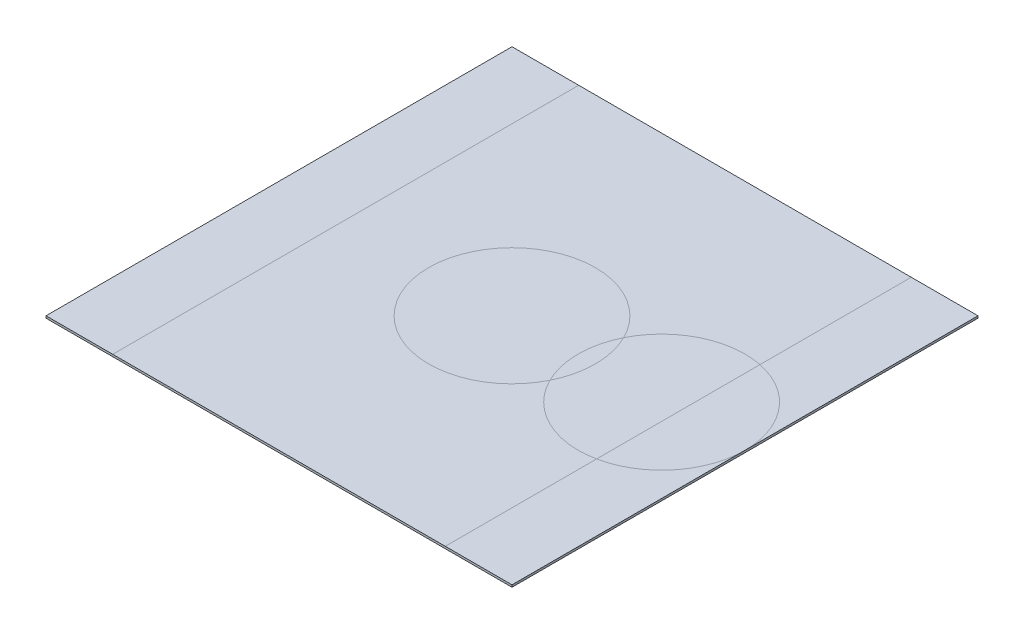
SolidWorks part; units mm, degrees
material "Zirconia"
ref_plane "Front Plane" through (0, 0, 0) normal (0, 0, 1) x (1, 0, 0)
ref_plane "Top Plane" through (0, 0, 0) normal (0, 1, 0) x (1, 0, 0)
ref_plane "Right Plane" through (0, 0, 0) normal (1, 0, 0) x (0, 0, -1)
sketch "Sketch1" plane through (0, 0, 0) normal (0, 1, 0) x (1, 0, 0)
  line L1 (-69.85, -69.85) -> (69.85, -69.85)
  line L2 (-69.85, -69.85) -> (-69.85, 69.85)
  line L3 (-69.85, 69.85) -> (69.85, 69.85)
  line L4 (69.85, -69.85) -> (69.85, 69.85)
  line L5 (-69.85, -69.85) -> (69.85, 69.85) construction
  line L6 (-69.85, 69.85) -> (69.85, -69.85) construction
  point P0 (0, 0)
  dimension "D1" = 139.7
extrude "Boss-Extrude1" add sketch "Sketch1" along normal mid plane 0.635
sketch "Sketch2" plane through (0, 0.3175, 0) normal (0, 1, 0) x (1, 0, 0)
  line L0 (69.85, -69.85) -> (69.85, 69.85) construction
  line L1 (-69.85, -69.85) -> (69.85, -69.85) construction
  line L2 (-69.85, 69.85) -> (-49.85, 69.85)
  line L3 (-69.85, 69.85) -> (-69.85, -69.85)
  line L4 (-69.85, -69.85) -> (-49.85, -69.85)
  line L5 (-49.85, 69.85) -> (-49.85, -69.85)
  line L7 (69.85, 69.85) -> (49.85, 69.85)
  line L8 (69.85, 69.85) -> (69.85, -69.85)
  line L9 (69.85, -69.85) -> (49.85, -69.85)
  line L10 (49.85, 69.85) -> (49.85, -69.85)
  circle A0 centre (0, 0) radius 25
  circle A1 centre (44.85, 0) radius 25
  dimension "D1" = 50
  dimension "D2" = 20
split line "Split Line1"
equation "\"panel_width\"= 5.5in"
equation "\"finger_joint_width\"= 30mm"
equation "\"D1@Sketch1\"=\"panel_width\""
